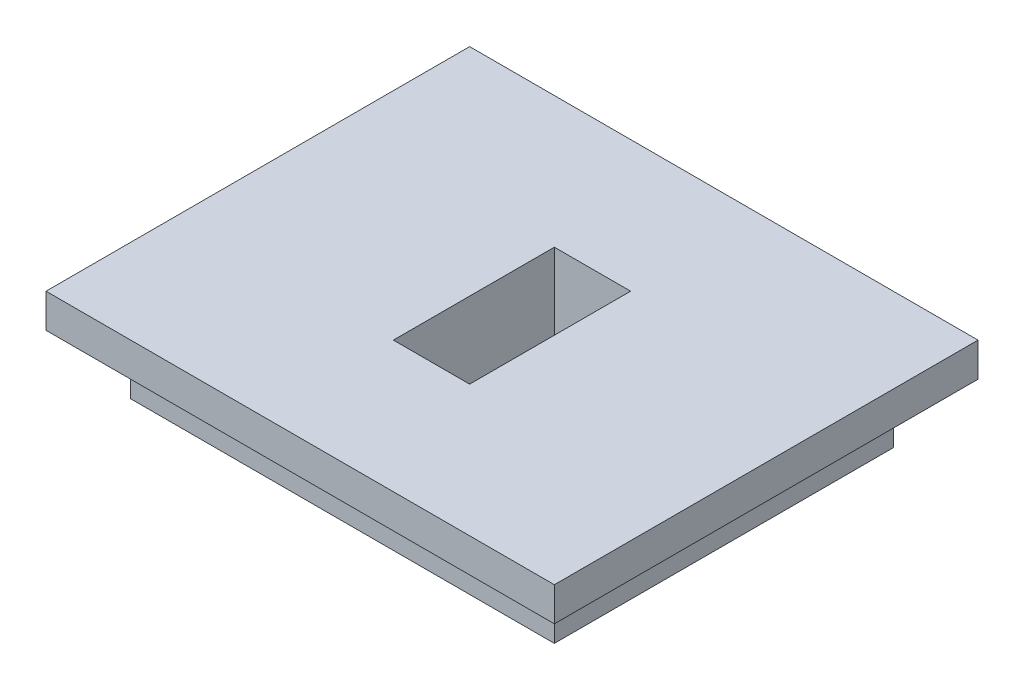
SolidWorks part; units mm, degrees
ref_plane "Front Plane" through (0, 0, 0) normal (0, 0, 1) x (1, 0, 0)
ref_plane "Top Plane" through (0, 0, 0) normal (0, 1, 0) x (1, 0, 0)
ref_plane "Right Plane" through (0, 0, 0) normal (1, 0, 0) x (0, 0, -1)
sketch "Sketch1" plane through (0, 0, 0) normal (0, 1, 0) x (1, 0, 0)
  line L1 (30, -25) -> (-30, -25)
  line L2 (30, -25) -> (30, 25)
  line L3 (30, 25) -> (-30, 25)
  line L4 (-30, -25) -> (-30, 25)
  line L5 (30, -25) -> (-30, 25) construction
  line L6 (30, 25) -> (-30, -25) construction
  point P0 (0, 0)
  dimension "D1" = 60
  dimension "D2" = 50
extrude "Boss-Extrude1" add sketch "Sketch1" along normal blind 4
ref_plane "Plane1" through (0, 0, 0) normal (0, -1, 0) x (-1, 0, 0)
sketch "Sketch2" plane through (0, 0, 0) normal (0, -1, 0) x (-1, 0, 0)
  line L1 (25, -20) -> (-25, -20)
  line L2 (25, -20) -> (25, 20)
  line L3 (25, 20) -> (-25, 20)
  line L4 (-25, -20) -> (-25, 20)
  line L5 (25, -20) -> (-25, 20) construction
  line L6 (25, 20) -> (-25, -20) construction
  point P0 (0, 0)
  dimension "D1" = 50
  dimension "D2" = 40
extrude "Boss-Extrude2" add sketch "Sketch2" along normal blind 7
ref_plane "Plane2" through (0, 4, 0) normal (0, 1, 0) x (1, 0, 0)
sketch "Sketch3" plane through (0, 4, 0) normal (0, 1, 0) x (1, 0, 0)
  line L1 (4.5, -9.5) -> (-4.5, -9.5)
  line L2 (4.5, -9.5) -> (4.5, 9.5)
  line L3 (4.5, 9.5) -> (-4.5, 9.5)
  line L4 (-4.5, -9.5) -> (-4.5, 9.5)
  line L5 (4.5, -9.5) -> (-4.5, 9.5) construction
  line L6 (4.5, 9.5) -> (-4.5, -9.5) construction
  point P0 (0, 0)
  dimension "D1" = 9
  dimension "D2" = 19
extrude "Cut-Extrude1" cut sketch "Sketch3" against normal blind 14
